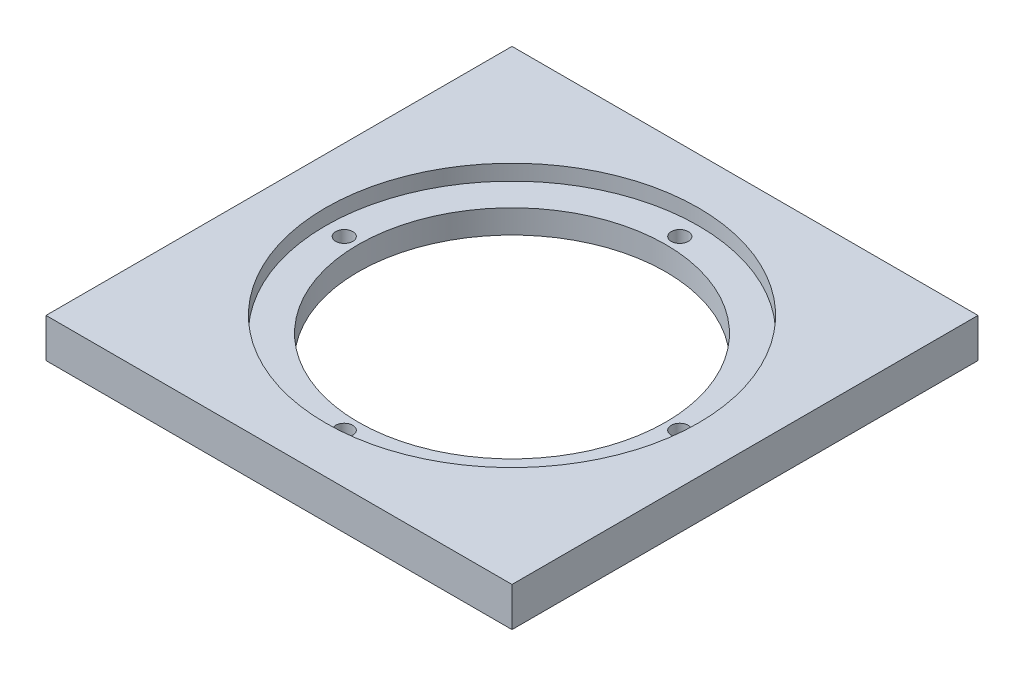
SolidWorks part; units mm, degrees
material "AISI 1045 Steel, cold drawn"
ref_plane "Frontal Plane" through (0, 0, 0) normal (0, 0, 1) x (1, 0, 0)
ref_plane "Horizontal Plane" through (0, 0, 0) normal (0, 1, 0) x (1, 0, 0)
ref_plane "Profile Plane" through (0, 0, 0) normal (1, 0, 0) x (0, 0, -1)
sketch "Sketch1" plane through (0, 0, 0) normal (0, 1, 0) x (1, 0, 0)
  line L1 (-75, -75) -> (75, -75)
  line L2 (-75, -75) -> (-75, 75)
  line L3 (-75, 75) -> (75, 75)
  line L4 (75, -75) -> (75, 75)
  line L5 (-75, -75) -> (75, 75) construction
  line L6 (-75, 75) -> (75, -75) construction
  circle A0 centre (0, 0) radius 49.5
  point P1 (0, 0)
  dimension "D3" = 99
  dimension "D1" = 150
  dimension "D2" = 150
extrude "Boss-Extrude1" add sketch "Sketch1" against normal blind 12.5984
sketch "Sketch2" plane through (0, 0, 0) normal (0, 1, 0) x (1, 0, 0)
  circle A0 centre (0, 0) radius 60
  dimension "D1" = 120
extrude "Cut-Extrude1" cut sketch "Sketch2" against normal blind 5
sketch "Sketch3" plane through (0, 0, 0) normal (0, 1, 0) x (1, 0, 0)
  line L0 (0, 0) -> (-54, 0) construction
  circle A0 centre (-54, 0) radius 2.75
  circle A1 centre (0, 54) radius 2.75
  circle A2 centre (54, 0) radius 2.75
  circle A3 centre (0, -54) radius 2.75
  dimension "D1" = 5.5
  dimension "D2" = 54
  dimension "D4" = 54
  dimension "D3" = 4
extrude "Cut-Extrude2" cut sketch "Sketch3" against normal through all both and the other way through all
equation "\"PinDiameter\"= 0"
equation "\"WallThickness\"= 0.5cm"
equation "\"BottomPlateX\"= 3ft"
equation "\"BottomPlateZ\"= 2ft"
equation "\"BottomPlateHoleD\"=((\"ArmPlateX\")^2+(\"ArmPlateDepth\")^2)^.5+ 10mm"
equation "\"ActuatorL\"= 35cm"
equation "\"ActuatorPinD\"= 6.35mm"
equation "\"ActuatorPinL\"= 15cm"
equation "\"Box-X\"= 40cm"
equation "\"Box-Z\"= 20cm"
equation "\"Box-Y\"= 30cm"
equation "\"ArmPlateThickness\"= .125in"
equation "\"ArmPlateX\"= 18in"
equation "\"ArmPlateDepth\"= 7.1875in"
equation "\"Arm1X\"= 5cm"
equation "\"Arm1L\"= 60cm"
equation "\"Arm2GAP\"= 5cm"
equation "\"Arm2L\"= 60cm"
equation "\"Arm2H\"= 5cm"
equation "\"Arm2Extension\"= 5cm"
equation "\"Arm3GAP\"= 5cm"
equation "\"Arm3L\"= 60cm"
equation "\"Arm3H\"= 5cm"
equation "\"Pin1-2L\"= \"Arm2GAP\" + (2 * \"WallThickness\")"
equation "\"Pin2-3L\"= \"Arm3GAP\" + (4 * \"WallThickness\")"
equation "\"DCMotor1D\"= 65mm"
equation "\"DCMotor1L\"= 215mm"
equation "\"DCMotor1ShaftL\"= 30mm"
equation "\"DCMotor2X\"= 68mm"
equation "\"DCMotor2D\"= 65mm"
equation "\"DCMotor2L\"= 208mm"
equation "\"DCMotor2ShaftL\"= 39mm"
equation "\"DCMotor2ShaftD\"= 15mm"
equation "\"BenchDepth\"= 5cm"
equation "\"BenchH\"= 10cm"
equation "\"BenchL\"= 15cm"
equation "\"PillowBlockW\"= 5cm"
equation "\"PillowBlockCenterH\"= \"DCMotor2X\"/2"
equation "\"EncoderRadius\"= 19mm"
equation "\"EncoderShaftL\"= 15mm"
equation "\"EncoderL\"= 33mm"
equation "\"EncoderHousingThickness\"= 7.5mm"
equation "\"TurntableID\"= 70mm"
equation "\"TurntableInner2*t\" = (\"TurntableOD\"-\"TurntableID\")*.25 - 1mm"
equation "\"TurntableInnerHoleRadius\"= \"TurntableID\"*.5 + \"TurntableInner2*t\"*.5"
equation "\"TurntableOD\"= 120mm"
equation "\"D1@Sketch1\"=\"TurntableOD\"+3cm"
equation "\"D2@Sketch1\"=\"TurntableOD\"+3cm"
equation "\"D1@Sketch2\"=\"TurntableOD\""
equation "\"D3@Sketch1\"=\"TurntableID\"+\"TurntableInner2*t\"*2+6mm"
equation "\"TurntableOuterHoleRadius\" = \"TurntableOD\"*.5 - ((\"TurntableOD\"-\"TurntableID\")*.25-.5mm)*.5"
equation "\"D2@Sketch3\"=\"TurntableOuterHoleRadius\""
